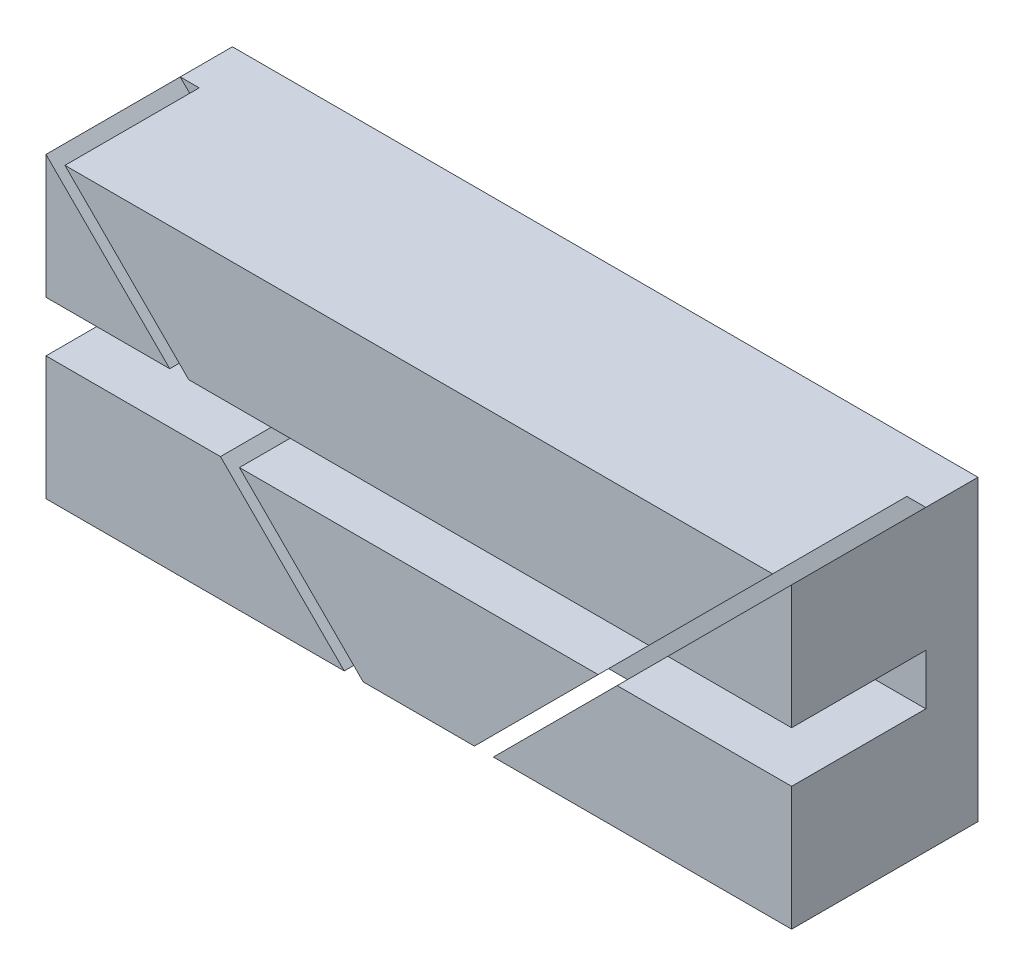
SolidWorks part; units mm, degrees
material "Custom Plastic"
ref_plane "X-Y Datum" through (0, 0, 0) normal (0, 0, 1) x (1, 0, 0)
ref_plane "X-Z Datum" through (0, 0, 0) normal (0, 1, 0) x (1, 0, 0)
ref_plane "Y-Z Datum" through (0, 0, 0) normal (1, 0, 0) x (0, 0, -1)
sketch "Sketch1" plane through (0, 0, 0) normal (0, 0, 1) x (1, 0, 0)
  line L0 (63.5, 25.4) -> (12.7, -25.4)
  line L1 (-63.5, 25.4) -> (63.5, 25.4)
  line L2 (-63.5, 25.4) -> (-63.5, -25.4)
  line L3 (-63.5, -25.4) -> (63.5, -25.4)
  line L4 (63.5, 25.4) -> (63.5, -25.4)
  line L5 (-63.5, 25.4) -> (63.5, -25.4) construction
  line L6 (-63.5, -25.4) -> (63.5, 25.4) construction
  line L7 (-63.5, 4.318) -> (63.5, 4.318)
  line L8 (-63.5, 4.318) -> (-63.5, -4.318)
  line L9 (-63.5, -4.318) -> (63.5, -4.318)
  line L10 (63.5, 4.318) -> (63.5, -4.318)
  line L11 (-63.5, 4.318) -> (63.5, -4.318) construction
  line L12 (-63.5, -4.318) -> (63.5, 4.318) construction
  line L13 (-63.5, 25.4) -> (-12.7, -25.4)
  line L14 (-60.2671, 25.4) -> (-9.4671, -25.4)
  line L15 (60.2671, 25.4) -> (9.4671, -25.4)
  line L16 (61.8836, 27.0164) -> (11.0836, -23.7836) construction
  line L17 (-61.8836, 27.0164) -> (-11.0836, -23.7836) construction
  point P0 (0, 0)
  point P6 (0, 0)
  point P17 (8.1813, -25.4)
  point P20 (-8.402, -25.4)
  dimension "D1" = 8.636
  dimension "D2" = 50.8
  dimension "D3" = 127
  dimension "D4" = 45
  dimension "D5" = 45
  dimension "D6" = 2.286
  dimension "D7" = 2.286
extrude "Boss-Extrude1" add sketch "Sketch1" along normal blind 31.75 contours L9 L0 L3 L4 | L15 L9 L14 L3 | L13 L9 L2 L3 | L9 L15 L3 L0 | L14 L9 L13 L3 | L15 L1 L14 L7 | L15 L7 L14 L9 | L0 L7 L4 | L0 L9 L4 L7 | L7 L15 L9 L0 | L1 L15 L7 L0 | L13 L2 L7 | L14 L1 L13 L7 | L13 L7 L2 L9 | L14 L7 L13 L9
sketch "Sketch2" plane through (0, 0, 31.75) normal (0, 0, 1) x (1, 0, 0)
  line L0 (60.2671, 25.4) -> (9.4671, -25.4) construction
  line L1 (-60.2671, 25.4) -> (-9.4671, -25.4) construction
  line L2 (-63.5, 25.4) -> (-12.7, -25.4) construction
  line L3 (-63.5, 25.4) -> (63.5, 25.4) construction
  line L4 (-63.5, 25.4) -> (-63.5, -25.4) construction
  line L5 (-63.5, -25.4) -> (63.5, -25.4) construction
  line L6 (63.5, 25.4) -> (63.5, -25.4) construction
  line L7 (63.5, 25.4) -> (12.7, -25.4) construction
  line L8 (-63.5, 4.318) -> (63.5, 4.318) construction
  line L9 (63.5, 4.318) -> (63.5, -4.318) construction
  line L10 (-63.5, -4.318) -> (63.5, -4.318) construction
  line L11 (-63.5, 4.318) -> (-63.5, -4.318) construction
  line L12 (60.2671, 25.4) -> (9.4671, -25.4)
  line L13 (-60.2671, 25.4) -> (-9.4671, -25.4)
  line L14 (-63.5, 25.4) -> (-12.7, -25.4)
  line L15 (-63.5, 25.4) -> (63.5, 25.4)
  line L16 (-63.5, 25.4) -> (-63.5, -25.4)
  line L17 (-63.5, -25.4) -> (63.5, -25.4)
  line L18 (63.5, 25.4) -> (63.5, -25.4)
  line L19 (63.5, 25.4) -> (12.7, -25.4)
  line L20 (-63.5, 4.318) -> (63.5, 4.318)
  line L21 (63.5, 4.318) -> (63.5, -4.318)
  line L22 (-63.5, -4.318) -> (63.5, -4.318)
  line L23 (-63.5, 4.318) -> (-63.5, -4.318)
  line M2 (63.5, 25.4) -> (-63.5, 25.4)
  line M4 (-63.5, -25.4) -> (63.5, -25.4)
extrude "Cut-Extrude1" cut sketch "Sketch2" against normal blind 22.86 contours L12 L20 L19 M2 | L12 L22 L19 L20 | L22 L12 L19 M4 | L13 L22 L12 L20 | L19 L22 L18 L20 | L22 L14 L13 M4 | L14 L22 L13 L20 | L14 L20 L13 M2 | L16 L22 L14 L20
